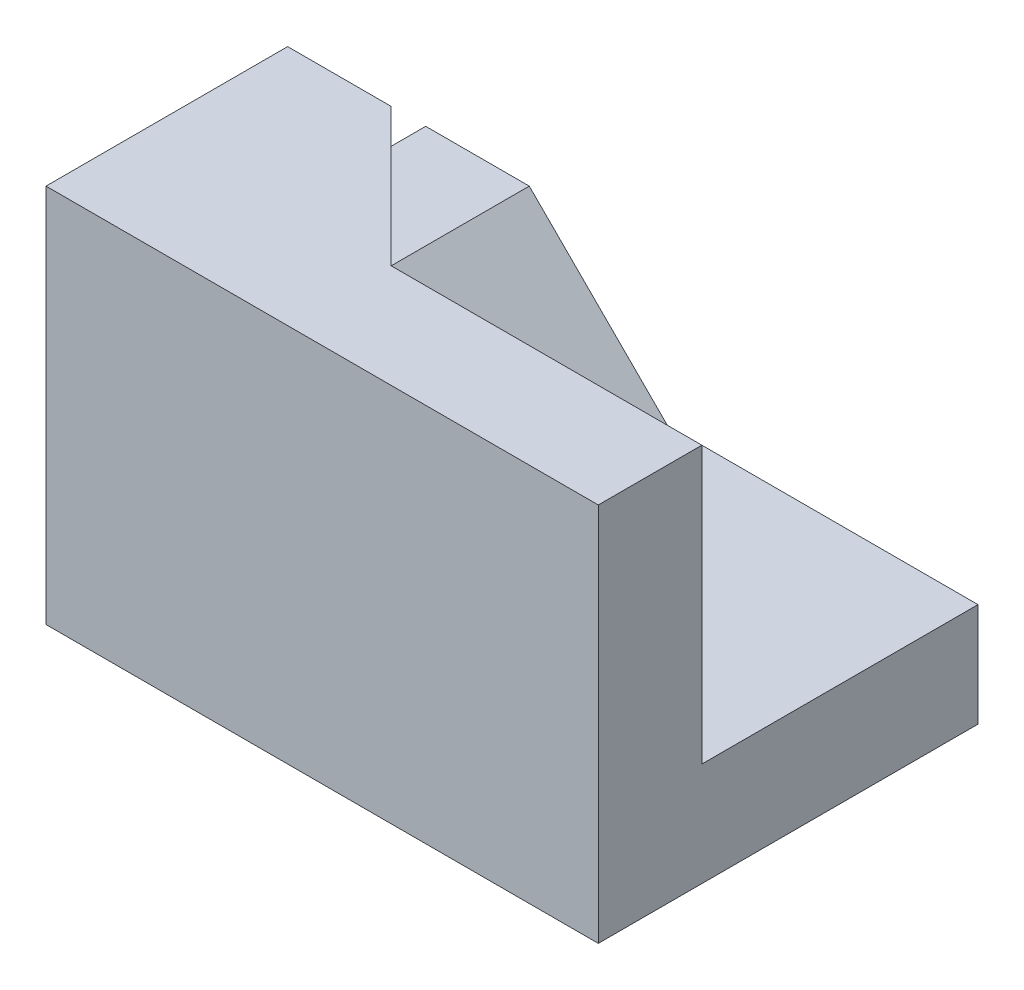
SolidWorks part; units mm, degrees
ref_plane "前视基准面" through (0, 0, 0) normal (0, 0, 1) x (1, 0, 0)
ref_plane "上视基准面" through (0, 0, 0) normal (0, 1, 0) x (1, 0, 0)
ref_plane "右视基准面" through (0, 0, 0) normal (1, 0, 0) x (0, 0, -1)
other "Configuration Table"
sketch "草图3" plane through (0, 0, 0) normal (0, 1, 0) x (1, 0, 0)
  line L1 (0, 0) -> (80, 0)
  line L2 (0, 0) -> (0, 55)
  line L3 (0, 55) -> (80, 55)
  line L4 (80, 0) -> (80, 55)
  dimension "D1" = 80
  dimension "D2" = 55
extrude "凸台-拉伸2" add sketch "草图3" along normal blind 55 contours L2 L1 L4 L3
ref_plane "基准面1" through (80, 0, 0) normal (1, 0, 0) x (0, 0, -1)
sketch "草图4" plane through (80, 0, 0) normal (1, 0, 0) x (0, 0, -1)
  line L1 (55, 55) -> (15, 55)
  line L2 (55, 55) -> (55, 15)
  line L3 (55, 15) -> (15, 15)
  line L4 (15, 55) -> (15, 15)
  dimension "D1" = 40
  dimension "D2" = 40
extrude "切除-拉伸2" cut sketch "草图4" against normal blind 45
ref_plane "基准面2" through (0, 0, 0) normal (-1, 0, 0) x (0, 0, 1)
sketch "草图5" plane through (0, 0, 0) normal (-1, 0, 0) x (0, 0, 1)
  line L1 (-55, 55) -> (-35, 55)
  line L2 (-55, 55) -> (-55, 35)
  line L3 (-55, 35) -> (-35, 35)
  line L4 (-35, 55) -> (-35, 35)
  dimension "D1" = 20
  dimension "D2" = 20
extrude "切除-拉伸5" cut sketch "草图5" against normal blind 15
loft "切除-放样11" cut section face at (35, 35, -35) section face at (15, 45, -45)
